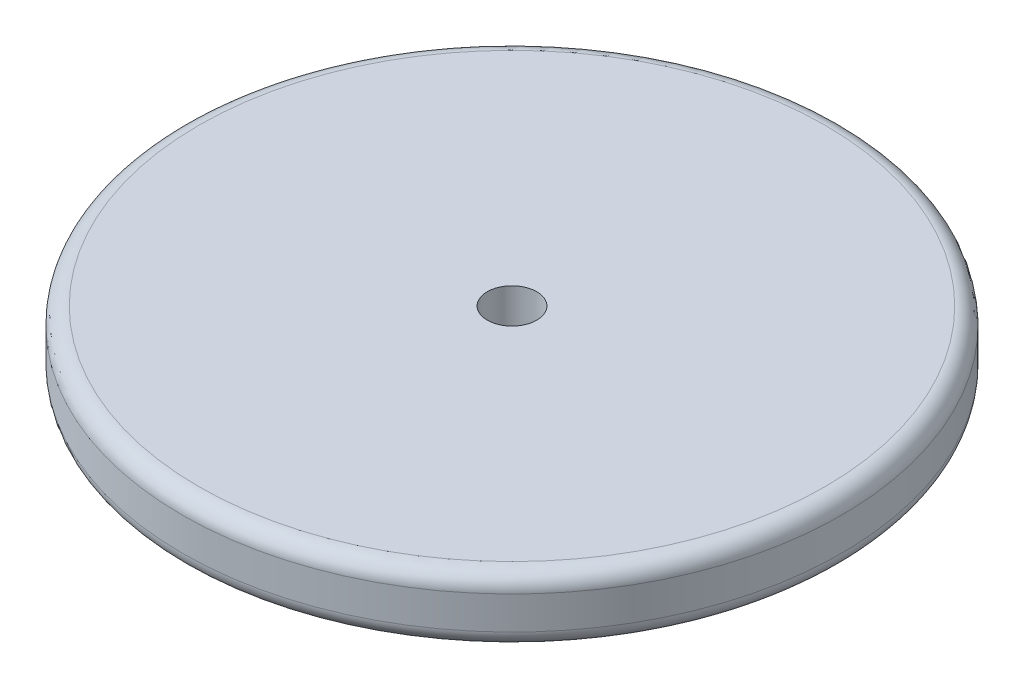
SolidWorks part; units mm, degrees
ref_plane "前视基准面" through (0, 0, 0) normal (0, 0, 1) x (1, 0, 0)
ref_plane "上视基准面" through (0, 0, 0) normal (0, 1, 0) x (1, 0, 0)
ref_plane "右视基准面" through (0, 0, 0) normal (1, 0, 0) x (0, 0, -1)
sketch "草图1" plane through (0, 0, 0) normal (0, 1, 0) x (1, 0, 0)
  circle A0 centre (0, 0) radius 7.5
  circle A1 centre (0, 0) radius 100
  dimension "D1" = 15
  dimension "D2" = 200
extrude "凸台-拉伸1" add sketch "草图1" along normal blind 20
fillet "圆角1" radius 5 2 edges at (0, 0, 100) (0, 20, 100)
